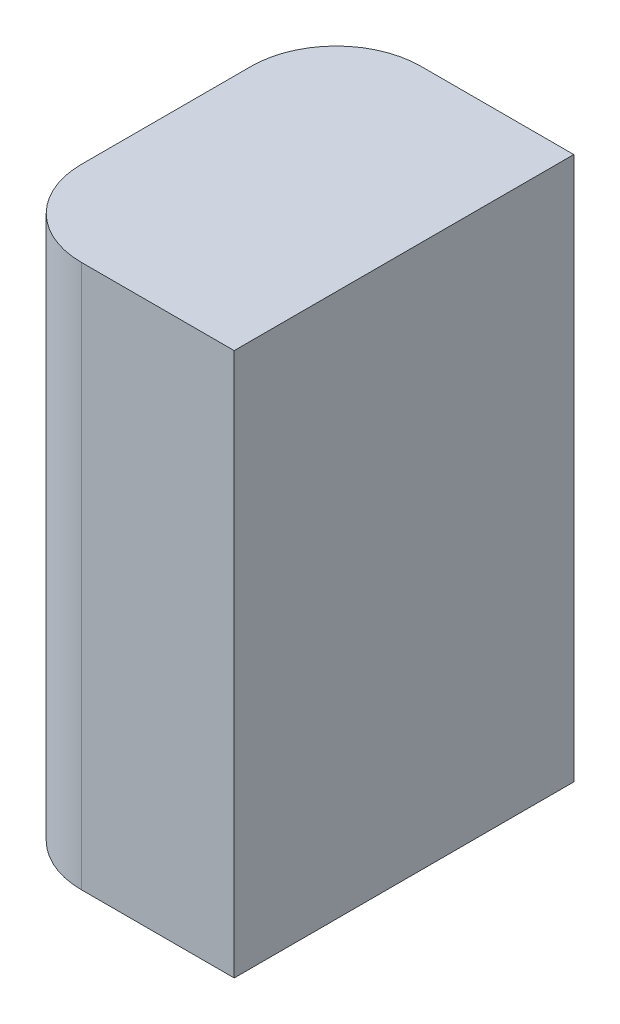
SolidWorks part; units mm, degrees
ref_plane "Front Plane" through (0, 0, 0) normal (0, 0, 1) x (1, 0, 0)
ref_plane "Top Plane" through (0, 0, 0) normal (0, 1, 0) x (1, 0, 0)
ref_plane "Right Plane" through (0, 0, 0) normal (1, 0, 0) x (0, 0, -1)
sketch "Sketch1" plane through (0, 0, 0) normal (0, 1, 0) x (1, 0, 0)
  line L1 (31.75, 0) -> (88.9, 0)
  line L2 (0, 31.75) -> (0, 95.25)
  line L3 (31.75, 127) -> (88.9, 127)
  line L4 (88.9, 0) -> (88.9, 127)
  arc A0 (31.75, 0) -> (0, 31.75) centre (31.75, 31.75) cw
  arc A1 (0, 95.25) -> (31.75, 127) centre (31.75, 95.25) cw
  point P7 (0, 0)
  point P10 (0, 127)
  dimension "D3" = 31.75
  dimension "D1" = 88.9
  dimension "D2" = 127
extrude "Boss-Extrude1" add sketch "Sketch1" along normal blind 203.2
